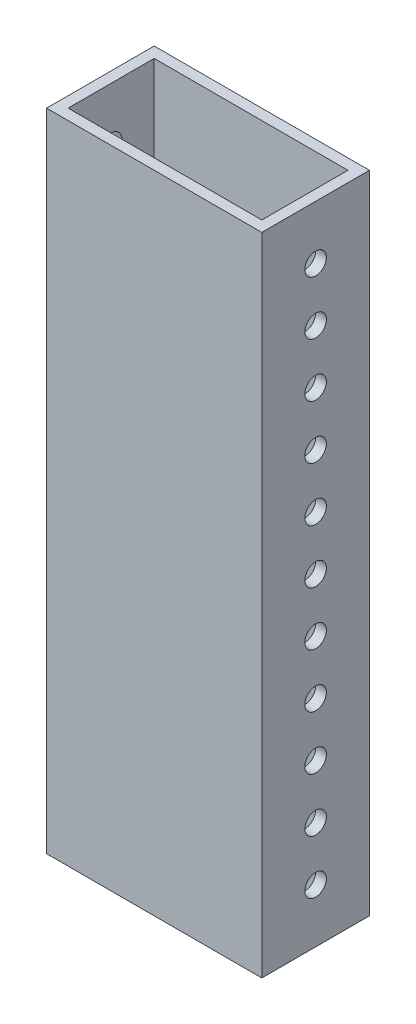
SolidWorks part; units mm, degrees
ref_plane "Front Plane" through (0, 0, 0) normal (0, 0, 1) x (1, 0, 0)
ref_plane "Top Plane" through (0, 0, 0) normal (0, 1, 0) x (1, 0, 0)
ref_plane "Right Plane" through (0, 0, 0) normal (1, 0, 0) x (0, 0, -1)
sketch "Sketch1" plane through (0, 0, 0) normal (0, 1, 0) x (1, 0, 0)
  line L1 (-59.9507, 17.7211) -> (-9.1507, 17.7211)
  line L2 (-59.9507, 17.7211) -> (-59.9507, -7.6789)
  line L3 (-59.9507, -7.6789) -> (-9.1507, -7.6789)
  line L4 (-9.1507, 17.7211) -> (-9.1507, -7.6789)
  line L5 (-59.9507, 17.7211) -> (-9.1507, -7.6789) construction
  line L6 (-59.9507, -7.6789) -> (-9.1507, 17.7211) construction
  line L7 (-57.4107, 15.1811) -> (-11.6907, 15.1811)
  line L8 (-57.4107, 15.1811) -> (-57.4107, -5.1389)
  line L9 (-57.4107, -5.1389) -> (-11.6907, -5.1389)
  line L10 (-11.6907, 15.1811) -> (-11.6907, -5.1389)
  line L11 (-57.4107, 15.1811) -> (-11.6907, -5.1389) construction
  line L12 (-57.4107, -5.1389) -> (-11.6907, 15.1811) construction
  point P0 (-34.5507, 5.0211)
  point P5 (-34.5507, 5.0211)
  dimension "D1" = 25.4
  dimension "D2" = 50.8
  dimension "D3" = 2.54
  dimension "D4" = 2.54
  dimension "D5" = 2.54
  dimension "D6" = 2.54
extrude "Boss-Extrude2" add sketch "Sketch1" along normal blind 152.4
sketch "Sketch2" plane through (-9.1507, 0, 0) normal (1, 0, 0) x (0, 0, -1)
  line L0 (-7.6789, 152.4) -> (17.7211, 152.4) construction
  line L1 (17.7211, 152.4) -> (17.7211, 0) construction
  circle A0 centre (5.0211, 139.7) radius 2.54
  circle A1 centre (5.0211, 127) radius 2.54
  circle A2 centre (5.0211, 114.3) radius 2.54
  circle A3 centre (5.0211, 101.6) radius 2.54
  circle A4 centre (5.0211, 88.9) radius 2.54
  circle A5 centre (5.0211, 76.2) radius 2.54
  circle A6 centre (5.0211, 63.5) radius 2.54
  circle A7 centre (5.0211, 50.8) radius 2.54
  circle A8 centre (5.0211, 38.1) radius 2.54
  circle A9 centre (5.0211, 25.4) radius 2.54
  circle A10 centre (5.0211, 12.7) radius 2.54
  point P6 (0, 0)
  dimension "D1" = 5.08
  dimension "D2" = 12.7
  dimension "D3" = 12.7
  dimension "D5" = 12.7
  dimension "D4" = 11
extrude "Cut-Extrude1" cut sketch "Sketch2" against normal blind 127
